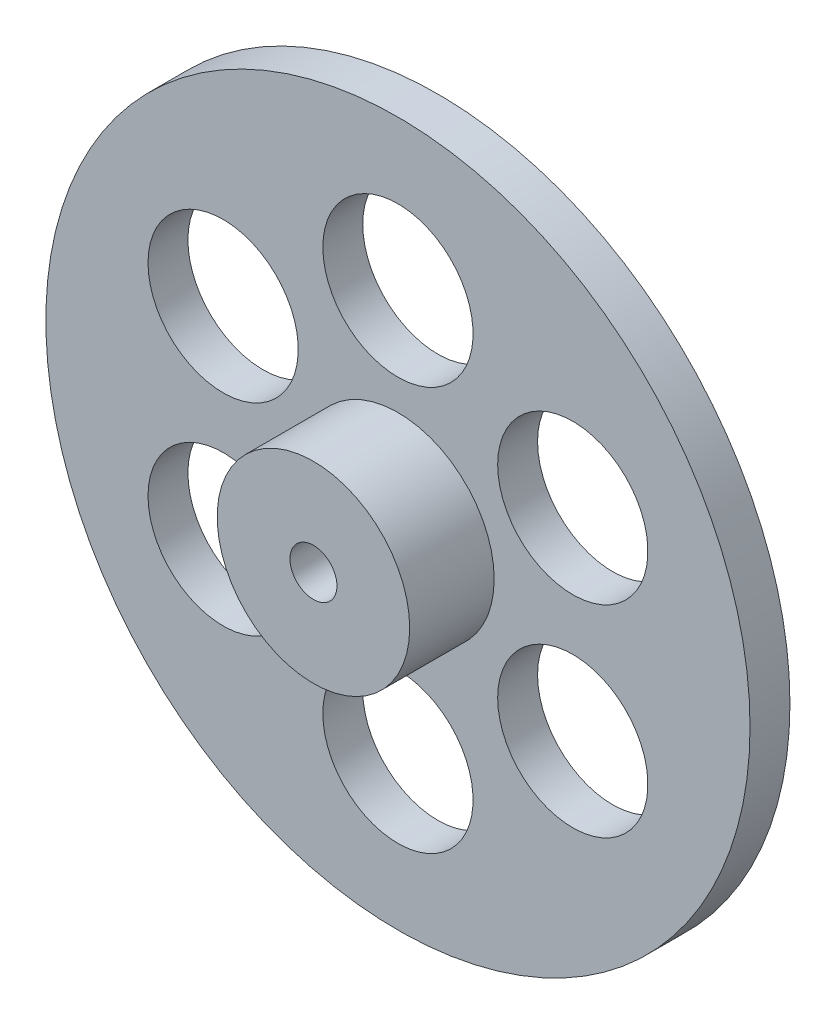
SolidWorks part; units mm, degrees
ref_plane "Front Plane" through (0, 0, 0) normal (0, 0, 1) x (1, 0, 0)
ref_plane "Top Plane" through (0, 0, 0) normal (0, 1, 0) x (1, 0, 0)
ref_plane "Right Plane" through (0, 0, 0) normal (1, 0, 0) x (0, 0, -1)
sketch "Sketch1" plane through (0, 0, 0) normal (1, 0, 0) x (0, 0, -1)
  line L0 (-128.6983, 0) -> (138.401, 0) construction
  line L1 (0, 0.5) -> (0, 2.05)
  line L2 (0, 55) -> (0, -55) construction
  line L3 (0, 2.05) -> (1.8, 2.05)
  line L4 (1.8, 2.05) -> (1.8, 7.5)
  line L5 (1.8, 7.5) -> (2.65, 7.5)
  line L6 (3, 1.5) -> (3, 0.5)
  line L7 (3, 0.5) -> (0, 0.5)
  line L8 (2.65, 7.5) -> (2.65, 1.5)
  line L9 (2.65, 1.5) -> (3, 1.5)
  dimension "D1" = 15
  dimension "D2" = 1
  dimension "D3" = 4.1
  dimension "D4" = 3
  dimension "D5" = 0.85
  dimension "D6" = 0.35
  dimension "D7" = 3
revolve "Revolve1" add sketch "Sketch1" angle 360 about L0
sketch "Sketch3" plane through (0, 0, -2.65) normal (0, 0, -1) x (-1, 0, 0)
  line L0 (0, 1.65) -> (0, -1.65) construction
  circle A0 centre (0, 4.3) radius 1.6
  circle A1 centre (0, 0) radius 7.5 construction
  dimension "D1" = 3.2
  dimension "D2" = 4.3
extrude "Cut-Extrude1" cut sketch "Sketch3" against normal through all
pattern_circular "CirPattern1" count 6 over 360 about axis through (0, 0, 0) along (0, 0, 1) of "Cut-Extrude1"
